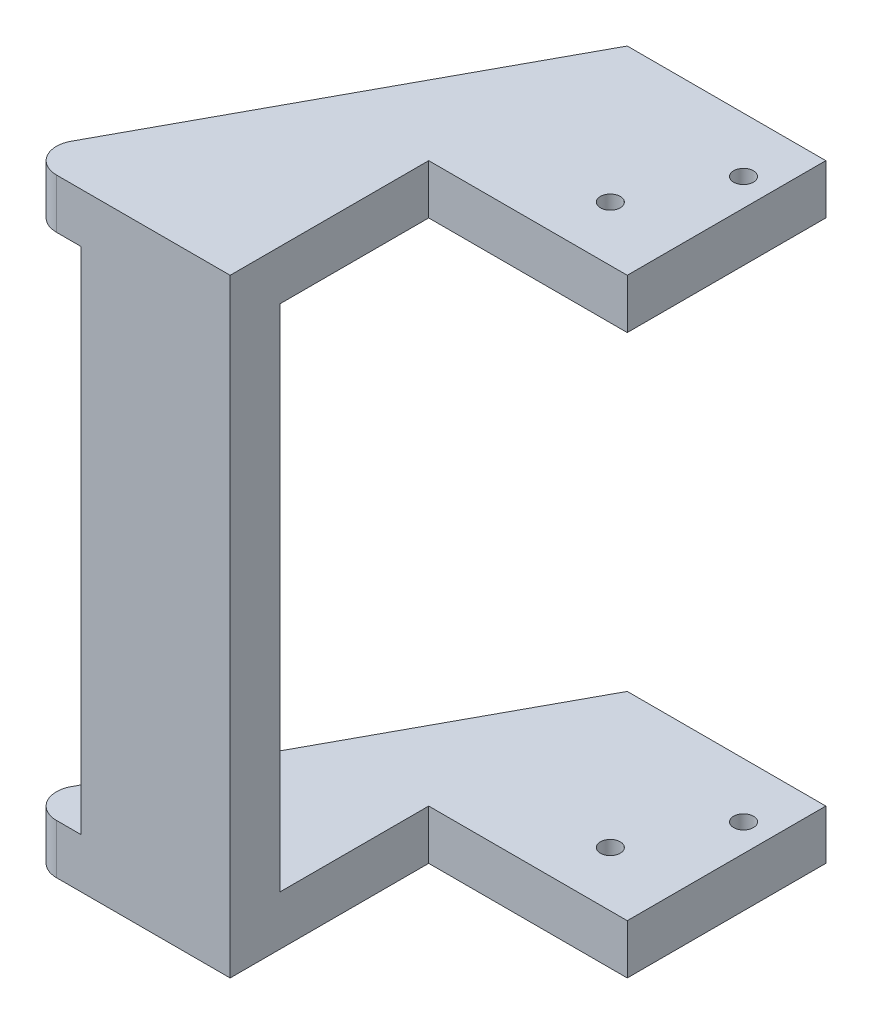
SolidWorks part; units mm, degrees
ref_plane "前视基准面" through (0, 0, 0) normal (0, 0, 1) x (1, 0, 0)
ref_plane "上视基准面" through (0, 0, 0) normal (0, 1, 0) x (1, 0, 0)
ref_plane "右视基准面" through (0, 0, 0) normal (1, 0, 0) x (0, 0, -1)
sketch "草图1" plane through (0, 0, 0) normal (0, 0, 1) x (1, 0, 0)
  line L0 (0, 0) -> (36740.6437, 0) construction
  line L1 (0, 0) -> (0, 36740.6437) construction
  line L3 (-20, 30.65) -> (20, 30.65)
  line L4 (-20, 30.65) -> (-20, -30.65)
  line L5 (-20, -30.65) -> (20, -30.65)
  line L6 (20, 30.65) -> (20, -30.65)
  dimension "D1" = 61.3
extrude "凸台-拉伸1" add sketch "草图1" along normal blind 40
sketch "草图2" plane through (0, 0, 40) normal (0, 0, 1) x (1, 0, 0)
  line L0 (0, 0) -> (50000, 0) construction
  line L1 (0, 0) -> (0, 50000) construction
  line L2 (20, -30.65) -> (20, 30.65) construction
  line L3 (0, 25.65) -> (20, 25.65)
  line L4 (0, 25.65) -> (0, -25.65)
  line L5 (0, -25.65) -> (20, -25.65)
  line L6 (20, 25.65) -> (20, -25.65)
  line L7 (20, 30.65) -> (-20, 30.65) construction
  dimension "D1" = 0
  dimension "D2" = 5
extrude "切除-拉伸1" cut sketch "草图2" against normal through all contours L4 L3 L6 L5
sketch "草图3" plane through (0, 0, 40) normal (0, 0, 1) x (1, 0, 0)
  line L0 (0, 0) -> (50000, 0) construction
  line L1 (0, 25.65) -> (0, -25.65) construction
  line L2 (0, 0) -> (0, 50000) construction
  line L3 (0, 25.65) -> (0, -25.65)
  line L4 (0, -25.65) -> (-15, -25.65)
  line L5 (-15, -25.65) -> (-15, 25.65)
  line L6 (-15, 25.65) -> (0, 25.65)
  line L7 (-20, 30.65) -> (-20, -30.65) construction
  line L8 (-15, 25.65) -> (-20, 25.65)
  line L9 (-20, 25.65) -> (-20, -25.65)
  line L10 (-20, -25.65) -> (-15, -25.65)
  point P4 (0, 0)
  line M11 (-20, 30.65) -> (-20, -30.65)
  dimension "D1" = 5
extrude "切除-拉伸2" cut sketch "草图3" against normal through all contours L10 L5 L8 M11
sketch "草图4" plane through (0, 0, 0) normal (1, 0, 0) x (0, 0, -1)
  line L0 (0, 0) -> (50000, 0) construction
  line L1 (0, 25.65) -> (0, -25.65) construction
  line L2 (0, 0) -> (0, 50000) construction
  line L3 (0, 25.65) -> (-40, 25.65) construction
  line L4 (-35, 25.65) -> (0, 25.65)
  line L5 (-35, 25.65) -> (-35, -25.65)
  line L6 (-35, -25.65) -> (0, -25.65)
  line L7 (0, 25.65) -> (0, -25.65)
  line L8 (-40, 25.65) -> (-40, -25.65) construction
  point P4 (0, 0)
  dimension "D1" = 5
extrude "切除-拉伸3" cut sketch "草图4" against normal through all
sketch "草图5" plane through (0, -30.65, 0) normal (0, -1, 0) x (1, 0, 0)
  line L0 (0, 40) -> (0, 20)
  line L1 (-20, 40) -> (20, 40) construction
  line L2 (0, 20) -> (20, 20)
  line L3 (20, 40) -> (20, 0) construction
  line L4 (-20, 40) -> (-20, 0) construction
  line L5 (-17.5, 40) -> (-20, 40)
  line L6 (-20, 40) -> (-20, 37.5)
  line L7 (0, 0) -> (-22.9129, 42.2347)
  line L8 (-20, 0) -> (20, 0) construction
  line L9 (-20, 37.5) -> (-20, 36.8655)
  circle A0 centre (-17.5, 37.5) radius 2.5
  line M4 (-20, 0) -> (20, 0)
  line M5 (20, 0) -> (20, 40)
  line M6 (20, 40) -> (-20, 40)
  line M7 (-20, 40) -> (-20, 0)
  dimension "D1" = 2.5
  dimension "D2" = 2.5
extrude "切除-拉伸5" cut sketch "草图5" against normal through all contours A0 L7 M7 | A0 M6 M7 | L7 M4 M7 | L0 L2 M5 M6
sketch "草图6" plane through (0, -30.65, 0) normal (0, -1, 0) x (1, 0, 0)
  line L0 (20, 10) -> (50020, 10) construction
  line L1 (20, 20) -> (20, 0) construction
  line L2 (20, 0) -> (-22340.6798, 44721.3595) construction
  circle A0 centre (12.765, 14.47) radius 1
  circle A1 centre (17.2371, 5.5257) radius 1
  point P8 (20, 10)
  dimension "D1" = 10
  dimension "D2" = 4.47
extrude "切除-拉伸6" cut sketch "草图6" against normal through all contours A0 | A1
